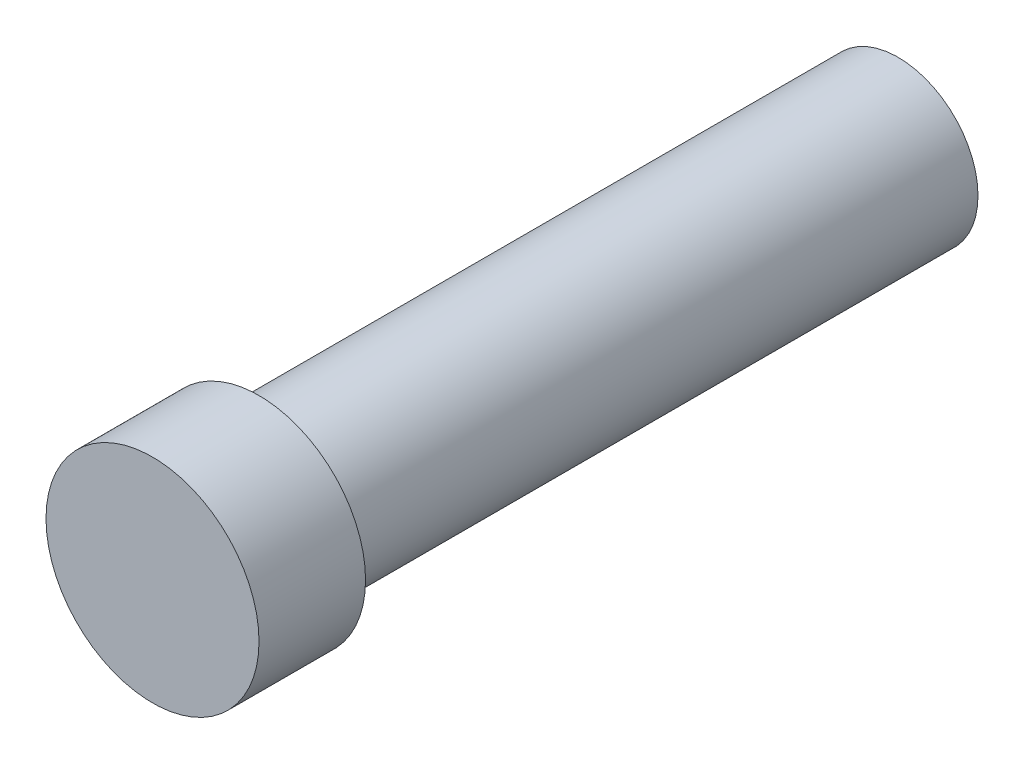
SolidWorks part; units mm, degrees
ref_plane "Alzado" through (0, 0, 0) normal (0, 0, 1) x (1, 0, 0)
ref_plane "Planta" through (0, 0, 0) normal (0, 1, 0) x (1, 0, 0)
ref_plane "Vista lateral" through (0, 0, 0) normal (1, 0, 0) x (0, 0, -1)
sketch "Croquis1" plane through (0, 0, 0) normal (0, 0, 1) x (1, 0, 0)
  circle A0 centre (0, 0) radius 1.5
extrude "Saliente-Extruir1" add sketch "Croquis1" along normal blind 12
sketch "Croquis2" plane through (0, 0, 12) normal (0, 0, 1) x (1, 0, 0)
  circle A0 centre (0, 0) radius 2
extrude "Saliente-Extruir2" add sketch "Croquis2" along normal blind 2
